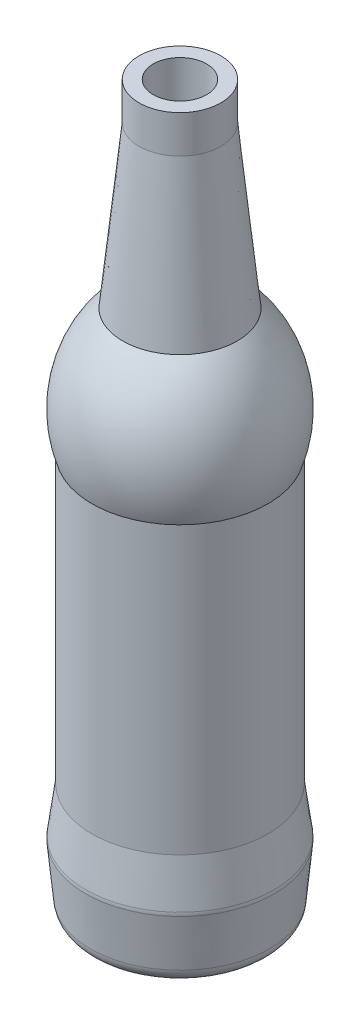
SolidWorks part; units mm, degrees
ref_plane "Piano frontale" through (0, 0, 0) normal (0, 0, 1) x (1, 0, 0)
ref_plane "Piano superiore" through (0, 0, 0) normal (0, 1, 0) x (1, 0, 0)
ref_plane "Piano destro" through (0, 0, 0) normal (1, 0, 0) x (0, 0, -1)
sketch "Schizzo1" plane through (0, 0, 0) normal (0, 0, 1) x (1, 0, 0)
  line L0 (0, 0) -> (0, 230) construction
  line L1 (0, 0) -> (-23.4536, 0)
  line L2 (-30, 0) -> (-30, 36) construction
  line L3 (-30, 36) -> (-28, 36) construction
  line L4 (-28, 36) -> (-28, 127)
  line L5 (-28, 127) -> (-30, 127) construction
  line L6 (-30, 127) -> (-30, 167) construction
  line L7 (-30, 167) -> (-18.25, 167) construction
  line L8 (-18.25, 167) -> (-13, 218)
  line L9 (-13, 218) -> (-13, 230)
  line L10 (-13, 230) -> (-8.5, 230)
  line L11 (-28, 36) -> (-29.9245, 21.5662)
  line L12 (-29.9458, 20.4313) -> (-28.431, 4.526)
  line L13 (-30, 0) -> (-28, 0) construction
  line L14 (0, 4.5) -> (-23.4536, 4.5)
  line L15 (-25.4661, 20.858) -> (-23.9513, 4.9526)
  line L16 (-23.5, 35.7013) -> (-25.464, 20.9715)
  line L17 (-23.5, 35.7013) -> (-23.5, 127.7572)
  line L18 (-13.9475, 164.8503) -> (-8.5, 217.769)
  line L19 (-8.5, 217.769) -> (-8.5, 225.5)
  line L20 (-8.5, 225.5) -> (-8.5, 230)
  line L21 (-8.5, 225.5) -> (0, 225.5) construction
  line L22 (-13, 230) -> (0, 230) construction
  line L23 (0, 4.5) -> (0, 0)
  arc A0 (-18.25, 167) -> (-28, 127) centre (8.608, 139.2651) ccw
  arc A1 (-29.9245, 21.5662) -> (-29.9458, 20.4313) centre (-24.9684, 20.9054) ccw
  arc A2 (-23.4536, 0) -> (-28.431, 4.526) centre (-23.4536, 5) cw
  arc A3 (-23.4536, 4.5) -> (-23.9513, 4.9526) centre (-23.4536, 5) cw
  arc A4 (-25.464, 20.9715) -> (-25.4661, 20.858) centre (-24.9684, 20.9054) ccw
  arc A5 (-13.9475, 164.8503) -> (-23.5, 127.7572) centre (8.608, 139.2651) ccw
  point P13 (-30, 21)
  point P14 (-28, 0)
  point P19 (-30, 21)
  dimension "D13" = 5
  dimension "D1" = 230
  dimension "D2" = 28
  dimension "D3" = 63
  dimension "D4" = 13
  dimension "D5" = 12
  dimension "D6" = 18.25
  dimension "D7" = 30
  dimension "D8" = 40
  dimension "D9" = 30
  dimension "D10" = 36
  dimension "D11" = 15
  dimension "D12" = 28
  dimension "D14" = 4.5
revolve "Rivoluzione1" add sketch "Schizzo1" angle 360 about L0
